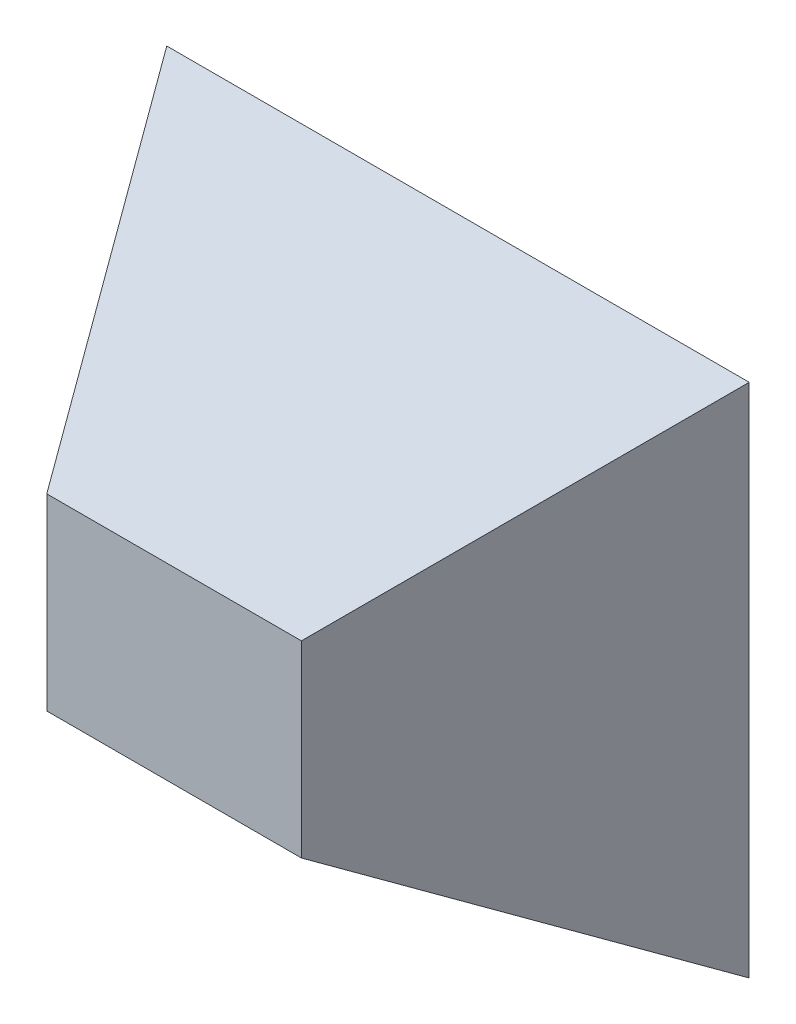
SolidWorks part; units mm, degrees
ref_plane "Front Plane" through (0, 0, 0) normal (0, 0, 1) x (1, 0, 0)
ref_plane "Top Plane" through (0, 0, 0) normal (0, 1, 0) x (1, 0, 0)
ref_plane "Right Plane" through (0, 0, 0) normal (1, 0, 0) x (0, 0, -1)
sketch "Sketch1" plane through (0, 0, 0) normal (0, 0, 1) x (1, 0, 0)
  line L1 (175, -155) -> (-175, -155)
  line L2 (175, -155) -> (175, 155)
  line L3 (175, 155) -> (-175, 155)
  line L4 (-175, -155) -> (-175, 155)
  line L5 (175, -155) -> (-175, 155) construction
  line L6 (175, 155) -> (-175, -155) construction
  point P0 (0, 0)
  dimension "D1" = 350
  dimension "D2" = 310
extrude "Boss-Extrude1" add sketch "Sketch1" along normal blind 170.6 draft 30
shell "Shell1" thickness 1.67
